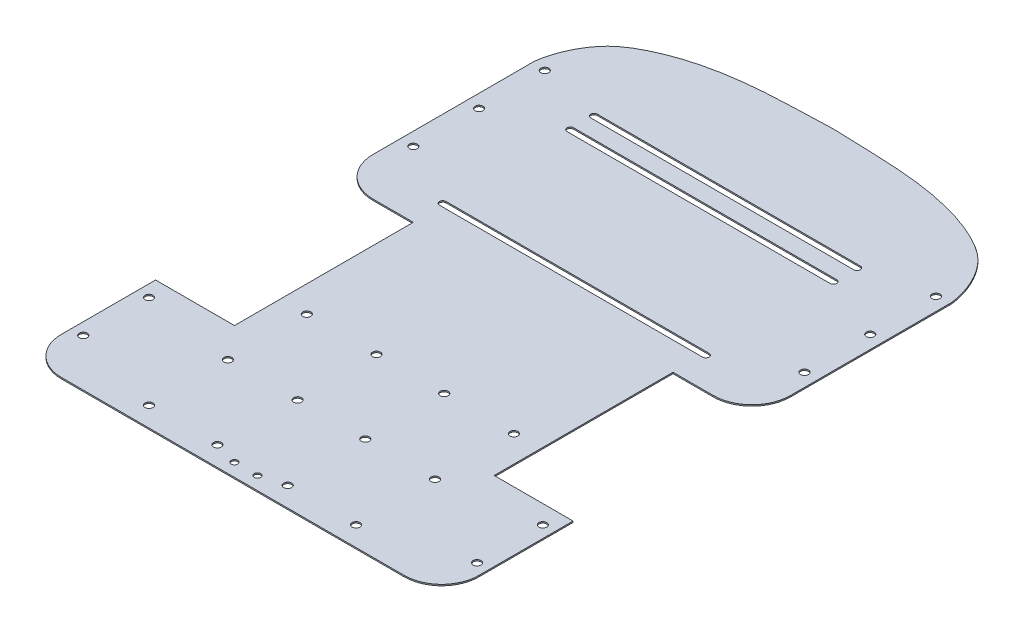
SolidWorks part; units mm, degrees
ref_plane "Front Plane" through (0, 0, 0) normal (0, 0, 1) x (1, 0, 0)
ref_plane "Top Plane" through (0, 0, 0) normal (0, 1, 0) x (1, 0, 0)
ref_plane "Right Plane" through (0, 0, 0) normal (1, 0, 0) x (0, 0, -1)
sketch "Sketch4" plane through (0, 0, 0) normal (0, 1, 0) x (1, 0, 0)
  line L0 (0, 128.6) -> (0, 0)
  line L1 (-65.209, 0) -> (0, 0)
  line L2 (-79.375, 14.166) -> (-79.375, 50)
  line L5 (622.9437, 519.1663) -> (1574.6175, 544.0867) construction
  line L6 (0, 228.6) -> (0, 188.6)
  line L7 (0, -55) -> (0, 55) construction
  line L9 (-79.375, 132.7) -> (-79.375, 193.786)
  line L10 (-49.375, 50) -> (-79.375, 50)
  line L12 (-49.375, 118) -> (-64.675, 118)
  line L14 (-50, 188.6) -> (0, 188.6)
  line L15 (-50, 186.1) -> (0, 186.1)
  line L16 (0, 186.1) -> (0, 179.6)
  line L17 (-50, 179.6) -> (0, 179.6)
  line L18 (-50, 177.1) -> (0, 177.1)
  line L19 (0, 177.1) -> (0, 131.1)
  line L20 (-50, 131.1) -> (0, 131.1)
  line L21 (-50, 128.6) -> (0, 128.6)
  line L22 (-49.375, 118) -> (-49.375, 50)
  arc A0 (-79.375, 14.166) -> (-65.209, 0) centre (-65.209, 14.166) ccw
  arc A1 (-79.375, 132.7) -> (-64.675, 118) centre (-64.675, 132.7) ccw
  circle A2 centre (-74.875, 43) radius 1.5
  circle A3 centre (-74.875, 18) radius 1.5
  circle A4 centre (-39.375, 7.5) radius 1.5
  circle A5 centre (-13.375, 7.5) radius 1.5
  circle A6 centre (-4.375, 5) radius 1.25
  circle A7 centre (-74.375, 143) radius 1.5
  circle A8 centre (-74.375, 168) radius 1.5
  circle A9 centre (-74.375, 193) radius 1.5
  arc A10 (-50, 188.6) -> (-50, 186.1) centre (-50, 187.35) ccw
  arc A11 (-50, 179.6) -> (-50, 177.1) centre (-50, 178.35) ccw
  arc A12 (-50, 131.1) -> (-50, 128.6) centre (-50, 129.85) ccw
  circle A13 centre (-39.375, 37.5) radius 1.5
  circle A14 centre (-39.375, 67.5) radius 1.5
  circle A15 centre (-12.875, 37.5) radius 1.5
  circle A16 centre (-12.875, 67.5) radius 1.5
  spline S0 degree 3 poles (-79.375, 193.786) (-78.784, 199.9641) (-73.9526, 211.6437) (-54.6605, 223.6018) (-29.5457, 228.1829) (-9.1881, 228.1715) (0, 228.6) knots 0 0 0 0 0.226113 0.32867 0.719907 1 1 1 1
  point P1 (-49.375, 50)
  dimension "D3" = 14.166
  dimension "D5" = 30
  dimension "D7" = 29.4
  dimension "D9" = 3
  dimension "D12" = 3
  dimension "D14" = 3
  dimension "D17" = 3
  dimension "D21" = 2.5
  dimension "D23" = 3
  dimension "D25" = 3
  dimension "D26" = 3
  dimension "D32" = 2.5
  dimension "D35" = 2.5
  dimension "D38" = 2.5
  dimension "D42" = 3
  dimension "D43" = 3
  dimension "D48" = 3
  dimension "D49" = 3
  dimension "D1" = 79.375
  dimension "D2" = 228.6
  dimension "D6" = 68
  dimension "D8" = 50
  dimension "D10" = 4.5
  dimension "D11" = 25
  dimension "4.5" = 4.5
  dimension "D13" = 40
  dimension "D15" = 7.5
  dimension "D16" = 7.5
  dimension "D18" = 26
  dimension "D19" = 5
  dimension "D20" = 9
  dimension "D22" = 25
  dimension "D24" = 5
  dimension "D27" = 25
  dimension "D28" = 25
  dimension "D29" = 5
  dimension "D30" = 5
  dimension "D31" = 50
  dimension "D33" = 40
  dimension "D34" = 2.5
  dimension "D36" = 9
  dimension "D37" = 50
  dimension "D39" = 48.5
  dimension "D40" = 50
  dimension "D41" = 30
  dimension "D44" = 30
  dimension "D45" = 26.5
  dimension "D46" = 30
  dimension "D47" = 30
  dimension "D50" = 30
extrude "Boss-Extrude2" add sketch "Sketch4" along normal blind 0.5
mirror "Mirror4" about plane through (0, 0.5, -177.1) normal (-1, 0, 0) of bodies 102
mirror "Mirror2"
